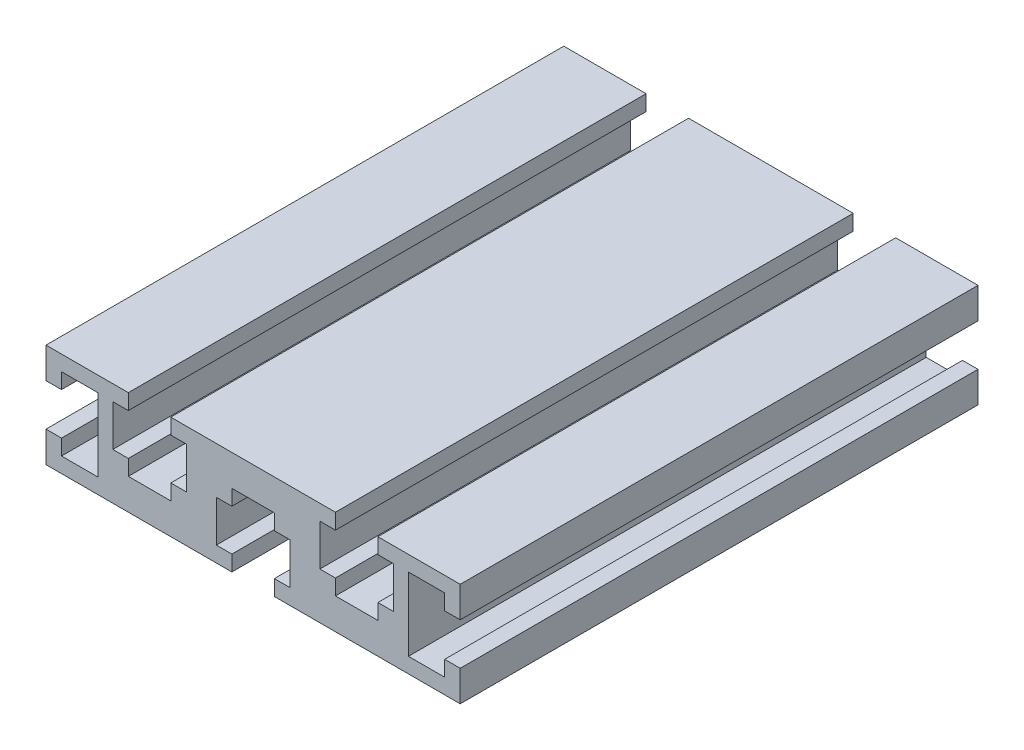
SolidWorks part; units mm, degrees
ref_plane "前视基准面" through (0, 0, 0) normal (0, 0, 1) x (1, 0, 0)
ref_plane "上视基准面" through (0, 0, 0) normal (0, 1, 0) x (1, 0, 0)
ref_plane "右视基准面" through (0, 0, 0) normal (1, 0, 0) x (0, 0, -1)
sketch "草图1" plane through (0, 0, 0) normal (0, 0, 1) x (1, 0, 0)
  line L0 (-12.2271, -6.2576) -> (-15.2271, -6.2576)
  line L1 (-15.2271, -6.2576) -> (-15.2271, 1.7424)
  line L2 (-15.2271, 1.7424) -> (-12.2271, 1.7424)
  line L3 (-12.2271, 1.7424) -> (-12.2271, 4.7424)
  line L4 (-12.2271, 4.7424) -> (-4.0271, 4.7424)
  line L5 (-4.0271, 4.7424) -> (-4.0271, 1.7424)
  line L6 (-4.0271, 1.7424) -> (-1.0271, 1.7424)
  line L7 (-1.0271, 1.7424) -> (-1.0271, -6.2576)
  line L8 (-1.0271, -6.2576) -> (-4.0271, -6.2576)
  line L9 (-4.0271, -6.2576) -> (-4.0271, -9.2576)
  line L10 (-4.0271, -9.2576) -> (31.8729, -9.2576)
  line L11 (31.8729, -9.2576) -> (31.8729, -3.3076)
  line L12 (31.8729, -3.3076) -> (28.8729, -3.3076)
  line L13 (28.8729, -3.3076) -> (28.8729, -6.3076)
  line L14 (28.8729, -6.3076) -> (21.8729, -6.3076)
  line L15 (21.8729, -6.3076) -> (21.8729, 7.7924)
  line L16 (21.8729, 7.7924) -> (28.8729, 7.7924)
  line L17 (28.8729, 7.7924) -> (28.8729, 4.7924)
  line L18 (28.8729, 4.7924) -> (31.8729, 4.7924)
  line L19 (31.8729, 4.7924) -> (31.8729, 10.7424)
  line L20 (31.8729, 10.7424) -> (15.9729, 10.7424)
  line L21 (15.9729, 10.7424) -> (15.9729, 7.7424)
  line L22 (15.9729, 7.7424) -> (18.9729, 7.7424)
  line L23 (18.9729, 7.7424) -> (18.9729, -0.2576)
  line L24 (18.9729, -0.2576) -> (15.9729, -0.2576)
  line L25 (15.9729, -0.2576) -> (15.9729, -3.2576)
  line L26 (15.9729, -3.2576) -> (7.7729, -3.2576)
  line L27 (7.7729, -3.2576) -> (7.7729, -0.2576)
  line L28 (7.7729, -0.2576) -> (4.7729, -0.2576)
  line L29 (4.7729, -0.2576) -> (4.7729, 7.7424)
  line L30 (4.7729, 7.7424) -> (7.7729, 7.7424)
  line L31 (7.7729, 7.7424) -> (7.7729, 10.7424)
  line L32 (7.7729, 10.7424) -> (-24.0271, 10.7424)
  line L33 (-24.0271, 10.7424) -> (-24.0271, 7.7424)
  line L34 (-24.0271, 7.7424) -> (-21.0271, 7.7424)
  line L35 (-21.0271, 7.7424) -> (-21.0271, -0.2576)
  line L36 (-21.0271, -0.2576) -> (-24.0271, -0.2576)
  line L37 (-24.0271, -0.2576) -> (-24.0271, -3.2576)
  line L38 (-24.0271, -3.2576) -> (-32.2271, -3.2576)
  line L39 (-32.2271, -3.2576) -> (-32.2271, -0.2576)
  line L40 (-32.2271, -0.2576) -> (-35.2271, -0.2576)
  line L41 (-35.2271, -0.2576) -> (-35.2271, 7.7424)
  line L42 (-35.2271, 7.7424) -> (-32.2271, 7.7424)
  line L43 (-32.2271, 7.7424) -> (-32.2271, 10.7424)
  line L44 (-32.2271, 10.7424) -> (-48.1271, 10.7424)
  line L45 (-48.1271, 10.7424) -> (-48.1271, 4.7924)
  line L46 (-48.1271, 4.7924) -> (-45.1271, 4.7924)
  line L47 (-45.1271, 4.7924) -> (-45.1271, 7.7924)
  line L48 (-45.1271, 7.7924) -> (-38.1271, 7.7924)
  line L49 (-38.1271, 7.7924) -> (-38.1271, -6.3076)
  line L50 (-38.1271, -6.3076) -> (-45.1271, -6.3076)
  line L51 (-45.1271, -6.3076) -> (-45.1271, -3.3076)
  line L52 (-45.1271, -3.3076) -> (-48.1271, -3.3076)
  line L53 (-48.1271, -3.3076) -> (-48.1271, -9.2576)
  line L54 (-48.1271, -9.2576) -> (-12.2271, -9.2576)
  line L55 (-12.2271, -9.2576) -> (-12.2271, -6.2576)
extrude "凸台-拉伸1" add sketch "草图1" along normal blind 100
